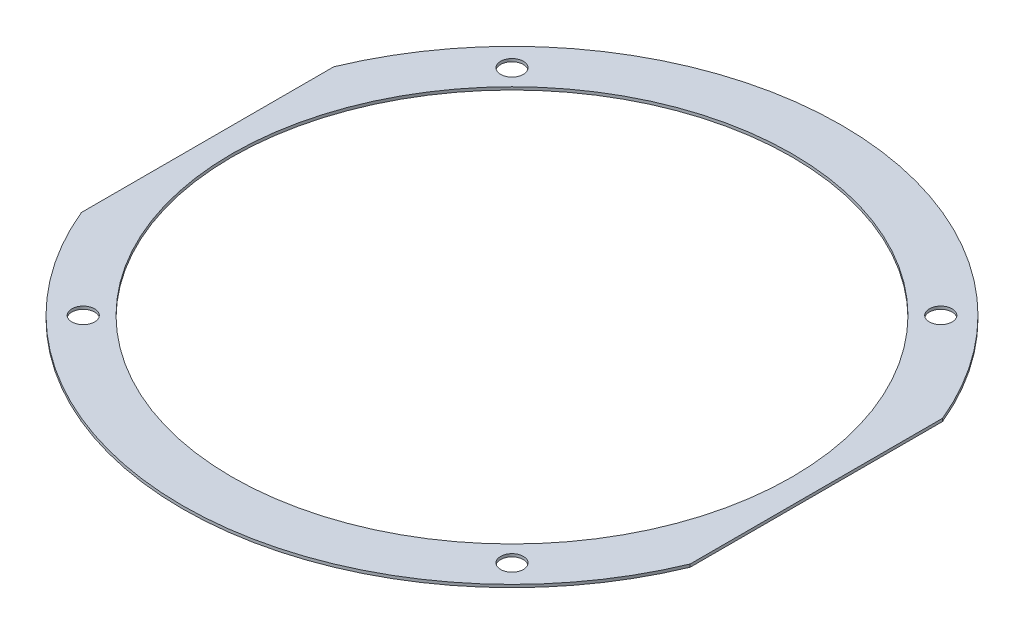
SolidWorks part; units mm, degrees
ref_plane "Front Plane" through (0, 0, 0) normal (0, 0, 1) x (1, 0, 0)
ref_plane "Top Plane" through (0, 0, 0) normal (0, 1, 0) x (1, 0, 0)
ref_plane "Right Plane" through (0, 0, 0) normal (1, 0, 0) x (0, 0, -1)
sketch "Sketch1" plane through (0, 0, 0) normal (0, 1, 0) x (1, 0, 0)
  line B0 (-26.75, 11.0884) -> (-26.75, -11.0884)
  line B1 (26.75, -11.0884) -> (26.75, 11.0884)
  arc B2 (26.75, 11.0884) -> (-26.75, 11.0884) centre (0, 0) ccw
  arc B3 (-26.75, -11.0884) -> (26.75, -11.0884) centre (0, 0) ccw
  circle B4 centre (18.8399, -18.8399) radius 1
  circle B5 centre (18.8399, 18.8399) radius 1
  circle B6 centre (-18.8399, 18.8399) radius 1
  circle B7 centre (-18.8399, -18.8399) radius 1
  circle B8 centre (0, 0) radius 24.6071
sketch_block_instance "Block-project00_blk00-1"
sketch_block "Block-project00_blk00"
extrude "Boss-Extrude1" add sketch "Sketch1" along normal blind 0.25
